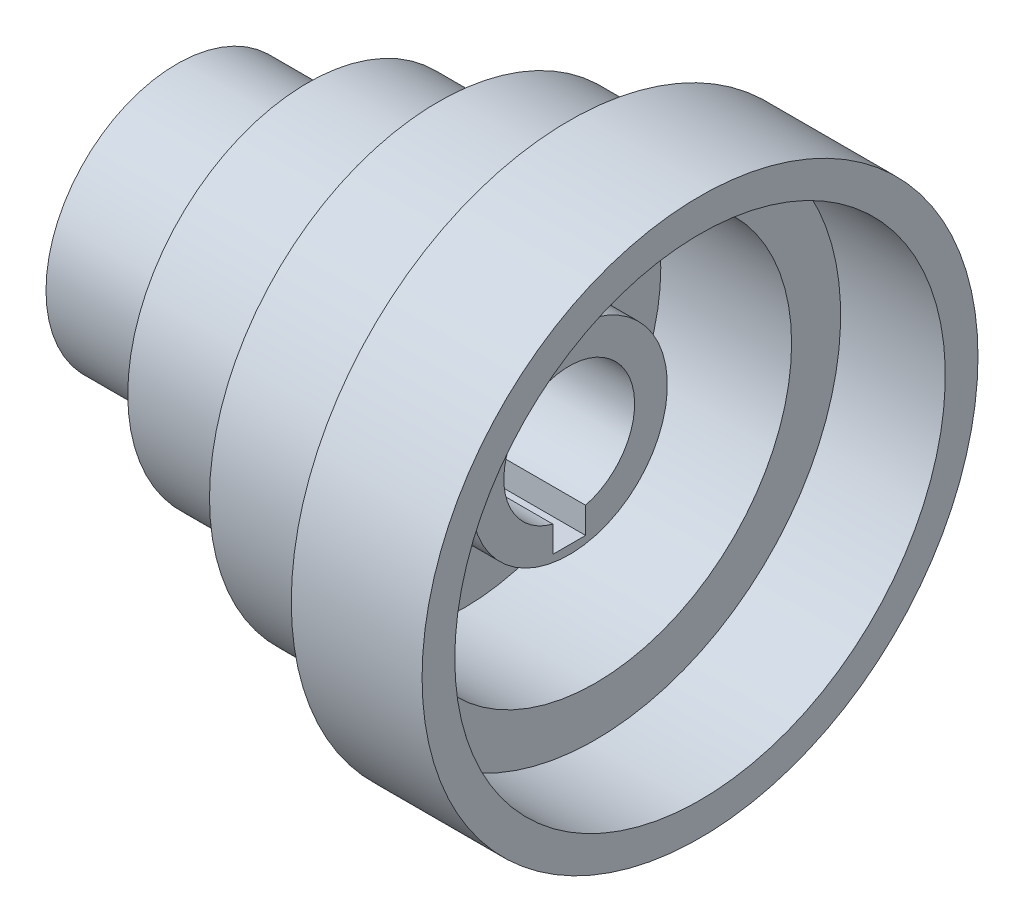
SolidWorks part; units mm, degrees
ref_plane "Front Plane" through (0, 0, 0) normal (0, 0, 1) x (1, 0, 0)
ref_plane "Top Plane" through (0, 0, 0) normal (0, 1, 0) x (1, 0, 0)
ref_plane "Right Plane" through (0, 0, 0) normal (1, 0, 0) x (0, 0, -1)
sketch "Sketch1" plane through (0, 0, 0) normal (0, 0, 1) x (1, 0, 0)
  line L0 (-79.3219, 0) -> (116.0352, 0) construction
  line L1 (-80, 20) -> (-80, 40)
  line L2 (-80, 40) -> (-40, 40)
  line L3 (-40, 40) -> (-40, 55)
  line L4 (-40, 55) -> (0, 55)
  line L5 (0, 55) -> (0, 70)
  line L14 (0, 70) -> (40, 70)
  line L15 (40, 70) -> (40, 85)
  line L16 (40, 85) -> (80, 85)
  line L20 (80, 85) -> (80, 75)
  line L21 (80, 75) -> (48, 75)
  line L22 (48, 75) -> (48, 60)
  line L23 (48, 60) -> (8, 60)
  line L24 (8, 60) -> (8, 45)
  line L25 (8, 45) -> (-32, 45)
  line L26 (-32, 45) -> (-32, 30)
  line L27 (-32, 30) -> (40, 30)
  line L28 (40, 30) -> (40, 20)
  line L29 (40, 20) -> (-80, 20)
  point P18 (-40, 47.5)
  dimension "D1" = 40
  dimension "D2" = 40
  dimension "D3" = 55
  dimension "D4" = 40
  dimension "D5" = 70
  dimension "D6" = 40
  dimension "D7" = 40
  dimension "D8" = 85
  dimension "D9" = 10
  dimension "D10" = 8
  dimension "D11" = 8
  dimension "D12" = 30
  dimension "D13" = 120
  dimension "D14" = 10
  dimension "D15" = 8
  dimension "D16" = 10
  dimension "D17" = 10
revolve "Revolve1" add sketch "Sketch1" angle 360 about L0
sketch "Sketch2" plane through (-80, 0, 0) normal (-1, 0, 0) x (0, 0, 1)
  line L0 (0, 20) -> (0, -20) construction
  line L1 (-5, -19.3649) -> (-5, -27.3649)
  line L2 (-5, -27.3649) -> (5, -27.3649)
  line L3 (5, -19.3649) -> (5, -27.3649)
  circle A0 centre (0, 0) radius 20 construction
  arc A1 (-5, -19.3649) -> (5, -19.3649) centre (0, 0) ccw
  point P9 (0, -27.3649)
  circle M5 centre (0, 0) radius 20
  dimension "D1" = 8
  dimension "D2" = 10
extrude "Cut-Extrude1" cut sketch "Sketch2" against normal through all contours L3 A1 L1 L2 M5
